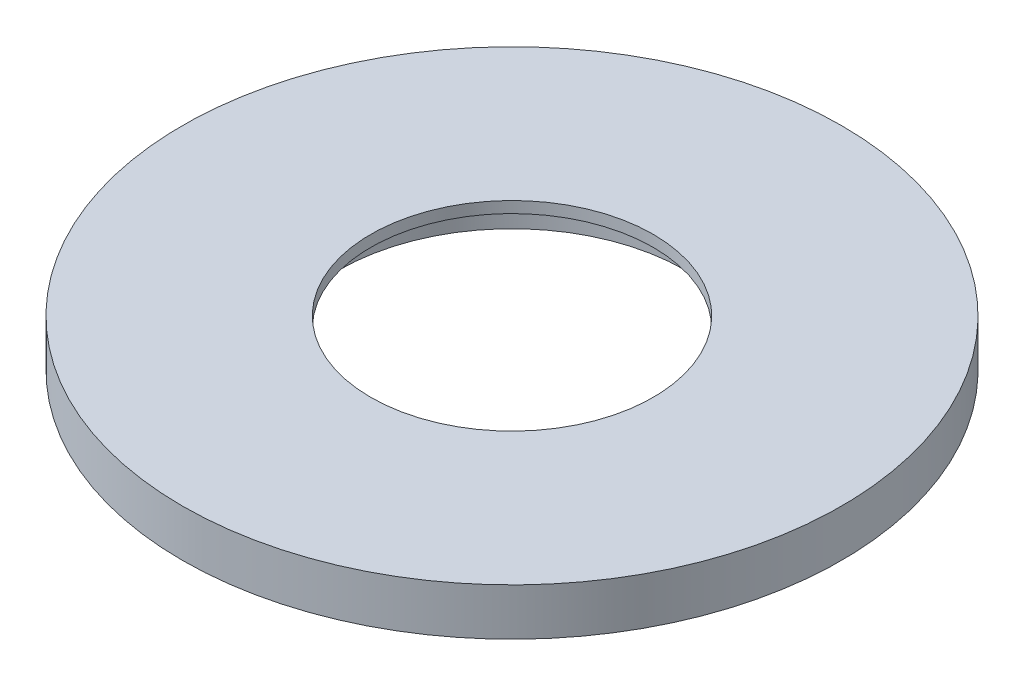
SolidWorks part; units mm, degrees
material "ABS"
ref_plane "Front Plane" through (0, 0, 0) normal (0, 0, 1) x (1, 0, 0)
ref_plane "Top Plane" through (0, 0, 0) normal (0, 1, 0) x (1, 0, 0)
ref_plane "Right Plane" through (0, 0, 0) normal (1, 0, 0) x (0, 0, -1)
sketch "Sketch2" plane through (0, 0, 0) normal (0, 1, 0) x (1, 0, 0)
  circle A0 centre (-21.3837, -0.6213) radius 17.5
  circle A5 centre (-21.3837, -0.6213) radius 9.2
  dimension "D1" = 18.4
  dimension "D2" = 35
extrude "Boss-Extrude1" add sketch "Sketch2" along normal blind 2.5
sketch "Sketch3" plane through (0, 2.5, 0) normal (0, 1, 0) x (1, 0, 0)
  circle A0 centre (-21.3837, -0.6213) radius 7.5
  circle M1 centre (-21.3837, -0.6213) radius 9.2
  dimension "D1" = 15
extrude "Boss-Extrude2" add sketch "Sketch3" against normal blind 0.6 contours A0 M1
sketch "Sketch4" plane through (0, 0, 0) normal (0, -1, 0) x (1, 0, 0)
  circle A0 centre (-21.5697, 15.5896) radius 1.67
  dimension "D1" = 3.34
extrude "Cut-Extrude1" cut sketch "Sketch4" against normal blind 1.15
pattern_circular "CirPattern1" count 4 over 360 about axis through (-21.3837, 0, 0.6213) along (0, 1, 0) of "Cut-Extrude1"
